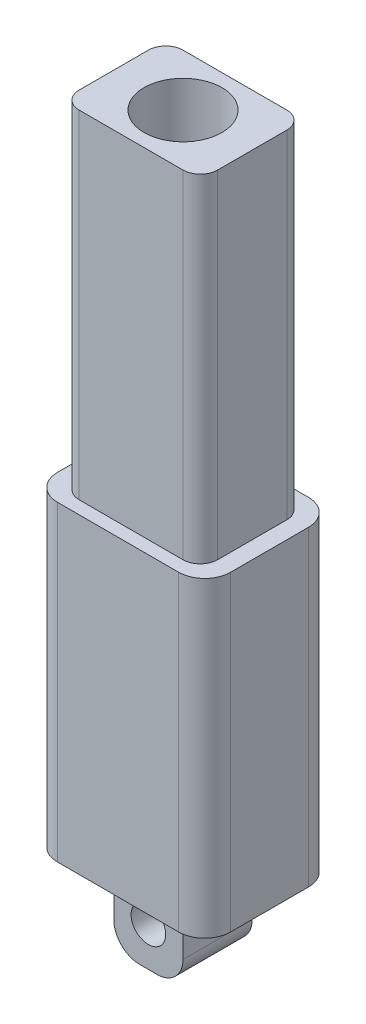
SolidWorks part; units mm, degrees
ref_plane "前视基准面" through (0, 0, 0) normal (0, 0, 1) x (1, 0, 0)
ref_plane "上视基准面" through (0, 0, 0) normal (0, 1, 0) x (1, 0, 0)
ref_plane "右视基准面" through (0, 0, 0) normal (1, 0, 0) x (0, 0, -1)
sketch "草图1" plane through (0, 0, 0) normal (0, 1, 0) x (1, 0, 0)
  line L1 (-10, -7.5) -> (10, -7.5)
  line L2 (-10, -7.5) -> (-10, 7.5)
  line L3 (-10, 7.5) -> (10, 7.5)
  line L4 (10, -7.5) -> (10, 7.5)
  line L5 (-10, -7.5) -> (10, 7.5) construction
  line L6 (-10, 7.5) -> (10, -7.5) construction
  point P0 (0, 0)
  dimension "D1" = 20
  dimension "D2" = 15
extrude "凸台-拉伸1" add sketch "草图1" along normal blind 36
sketch "草图2" plane through (0, 0, 0) normal (0, 0, 1) x (1, 0, 0)
  line L0 (0, 0) -> (0, -12.3824) construction
  line L1 (-10, 0) -> (10, 0) construction
  line L2 (4, 0) -> (4, -9)
  line L3 (4, -9) -> (-4, -9)
  line L4 (-4, 0) -> (-4, -9)
  line L5 (-4, 0) -> (4, 0)
  circle A0 centre (0, -4.5) radius 2
  point P11 (0, -9)
  dimension "D1" = 4.5
  dimension "D2" = 4
  dimension "D3" = 9
  dimension "D4" = 8
extrude "凸台-拉伸2" add sketch "草图2" along normal mid plane 8
fillet "圆角1" radius 3 4 edges at (4, 0, 0) (-4, 0, 0) (-4, -9, 0) (4, -9, 0)
sketch "草图3" plane through (0, 0, 0) normal (0, 0, 1) x (1, 0, 0)
  line L0 (0, 36) -> (0, 75.0807) construction
  line L1 (-10, 36) -> (10, 36) construction
  line L3 (-8, 75) -> (8, 75)
  line L4 (-8, 75) -> (-8, 36)
  line L5 (-8, 36) -> (8, 36)
  line L6 (8, 75) -> (8, 36)
  line L7 (-8, 75) -> (8, 36) construction
  line L8 (-8, 36) -> (8, 75) construction
  point P5 (0, 55.5)
  dimension "D1" = 39
  dimension "D2" = 16
extrude "凸台-拉伸3" add sketch "草图3" along normal mid plane 12 separate body
sketch "草图4" plane through (0, 75, 0) normal (0, 1, 0) x (1, 0, 0)
  circle A0 centre (0, 0) radius 4.5
  dimension "D1" = 9
extrude "切除-拉伸1" cut sketch "草图4" against normal blind 40
fillet "圆角2" radius 3 4 edges at (10, 18, 7.5) (10, 18, -7.5) (-10, 18, -7.5) (-10, 18, 7.5)
fillet "圆角3" radius 2 4 edges at (8, 55.5, -6) (-8, 55.5, -6) (8, 55.5, 6) (-8, 55.5, 6)
